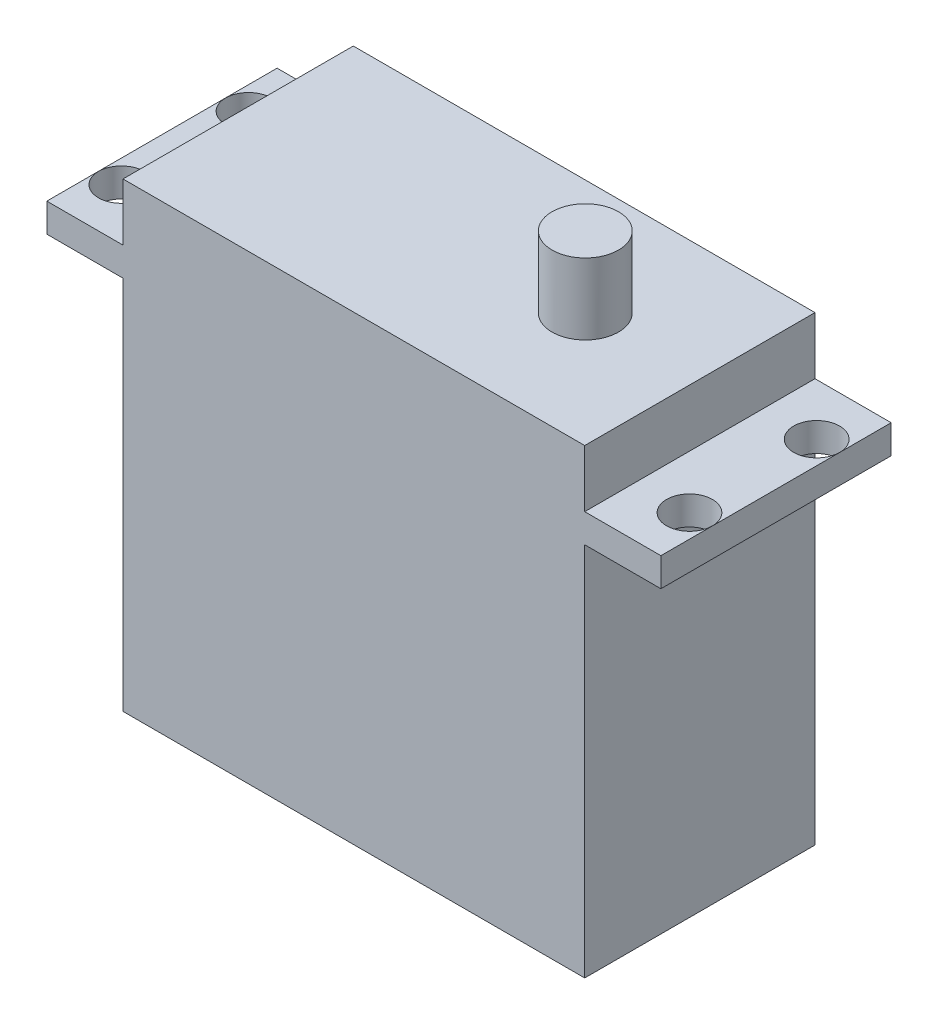
SolidWorks part; units mm, degrees
ref_plane "Front Plane" through (0, 0, 0) normal (0, 0, 1) x (1, 0, 0)
ref_plane "Top Plane" through (0, 0, 0) normal (0, 1, 0) x (1, 0, 0)
ref_plane "Right Plane" through (0, 0, 0) normal (1, 0, 0) x (0, 0, -1)
sketch "Sketch1" plane through (0, 0, 0) normal (0, 1, 0) x (1, 0, 0)
  line L1 (-20.15, -10.05) -> (20.15, -10.05)
  line L2 (-20.15, -10.05) -> (-20.15, 10.05)
  line L3 (-20.15, 10.05) -> (20.15, 10.05)
  line L4 (20.15, -10.05) -> (20.15, 10.05)
  line L5 (-20.15, -10.05) -> (20.15, 10.05) construction
  line L6 (-20.15, 10.05) -> (20.15, -10.05) construction
  point P0 (0, 0)
  dimension "D1" = 20.1
  dimension "D2" = 40.3
extrude "Boss-Extrude1" add sketch "Sketch1" along normal blind 40.25
sketch "Sketch2" plane through (0, 40.25, 0) normal (0, 1, 0) x (1, 0, 0)
  line L0 (20.15, 0) -> (10.15, 0) construction
  line L1 (20.15, -10.05) -> (20.15, 10.05) construction
  circle A0 centre (10.15, 0) radius 2.9
  dimension "D2" = 5.8
  dimension "D1" = 10
extrude "Boss-Extrude2" add sketch "Sketch2" along normal blind 6.2
sketch "Sketch3" plane through (0, 40.25, 0) normal (0, 1, 0) x (1, 0, 0)
  line L0 (-26.8, 0) -> (26.8, 0) construction
  line L1 (-20.15, 10.05) -> (-26.8, 10.05)
  line L2 (-20.15, -10.05) -> (-26.8, -10.05)
  line L3 (-26.8, -10.05) -> (-26.8, 10.05)
  line L4 (20.15, 10.05) -> (26.8, 10.05)
  line L5 (26.8, 10.05) -> (26.8, -10.05)
  line L6 (26.8, -10.05) -> (20.15, -10.05)
  line L7 (-20.15, 10.05) -> (-20.15, -10.05)
  line L8 (20.15, 10.05) -> (20.15, -10.05)
  line L9 (-26.8, 3.75) -> (-26.8, -3.75)
  line L10 (0, -10.05) -> (0, 10.05) construction
  line L11 (-20.15, -10.05) -> (20.15, -10.05) construction
  line L12 (20.15, 10.05) -> (-20.15, 10.05) construction
  circle A0 centre (-24.7944, 5.55) radius 2
  circle A1 centre (-24.7944, -5.55) radius 2
  circle A2 centre (24.7944, -5.55) radius 2
  circle A3 centre (24.7944, 5.55) radius 2
  point P4 (0, 0)
  point P20 (-26.8, 0)
  line M4 (20.15, -10.05) -> (20.15, 10.05)
  line M6 (-20.15, 10.05) -> (-20.15, -10.05)
  dimension "D4" = 4
  dimension "D5" = 4.5
  dimension "D1" = 53.6
  dimension "D2" = 6.65
  dimension "D3" = 7.5
extrude "Boss-Extrude3" add sketch "Sketch3" against normal blind 2.5 from offset 5 contours L3 L2 L1 A0 A1 M6 | L6 L5 L4 A2 A3 M4
